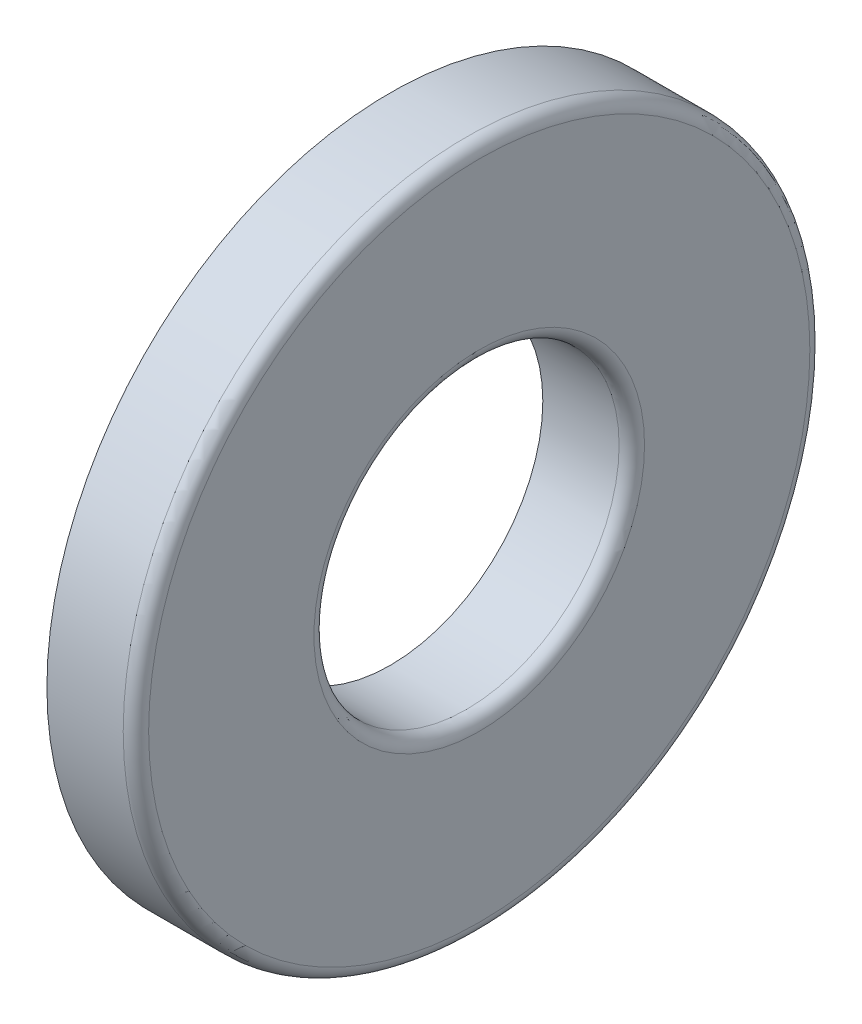
SolidWorks part; units mm, degrees
ref_plane "Plan1" through (0, 0, 0) normal (0, 0, 1) x (1, 0, 0)
ref_plane "Plan2" through (0, 0, 0) normal (0, 1, 0) x (1, 0, 0)
ref_plane "Plan3" through (0, 0, 0) normal (1, 0, 0) x (0, 0, -1)
sketch "Esquisse1" plane through (0, 0, 0) normal (0, 0, 1) x (1, 0, 0)
  line L0 (0, 0) -> (0, 7.3417)
  line L1 (0, 13.5) -> (3.5, 13.5)
  line L2 (3.5, 13.5) -> (3.5, 0)
  line L3 (-2.5, 0) -> (7, 0) construction
  line L4 (0, 10.6583) -> (0, 13.5)
  line L5 (0, 0) -> (3.5, 0)
  arc A0 (0, 7.3417) -> (0, 10.6583) centre (-2.5, 9) ccw
  dimension "D3" = 6
  dimension "D1" = 13.5
  dimension "D2" = 3.5
  dimension "D4" = 2.5
  dimension "D5" = 9
revolve "Base-Révolution" add sketch "Esquisse1" angle 360 about L3
fillet "Congé1" radius 0.5
sketch "Esquisse2" plane through (3.5, 0, 0) normal (1, 0, 0) x (0, 0, -1)
  circle A0 centre (0, 0) radius 6
  dimension "D1" = 12
extrude "Enlèv. mat.-Extru.1" cut sketch "Esquisse2" against normal through all
fillet "Congé2" radius 0.5
